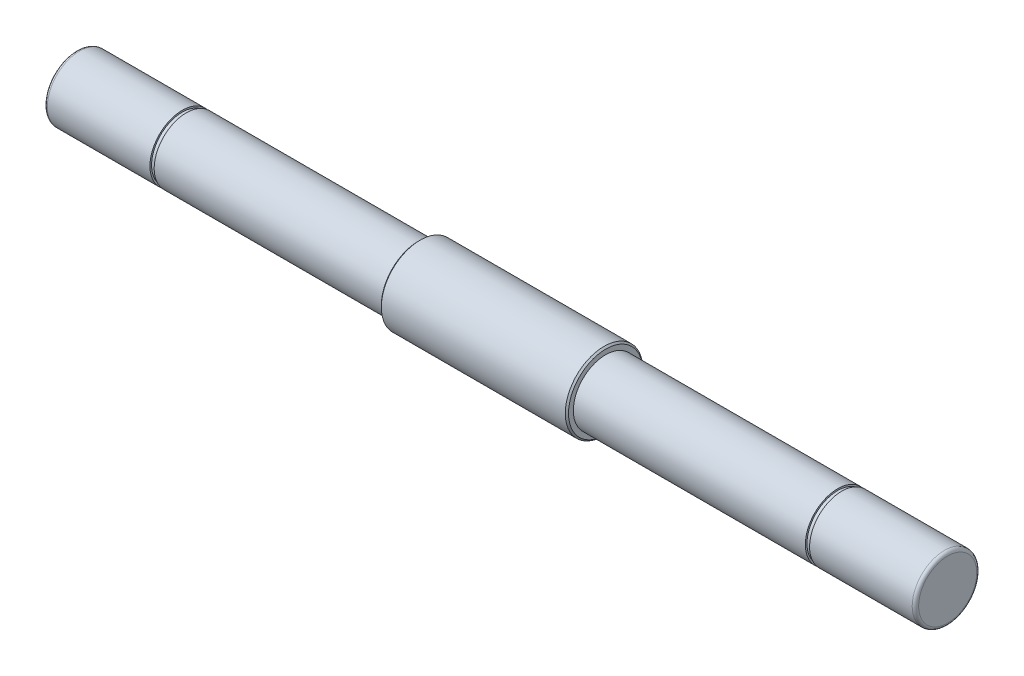
SolidWorks part; units mm, degrees
ref_plane "Front Plane" through (0, 0, 0) normal (0, 0, 1) x (1, 0, 0)
ref_plane "Top Plane" through (0, 0, 0) normal (0, 1, 0) x (1, 0, 0)
ref_plane "Right Plane" through (0, 0, 0) normal (1, 0, 0) x (0, 0, -1)
sketch "Sketch1" plane through (0, 0, 0) normal (0, 1, 0) x (1, 0, 0)
  line L0 (-135, 0) -> (135, 0) construction
  line L1 (-135, 0) -> (-135, 10)
  line L4 (0, 0) -> (0, 68.7304) construction
  line L5 (-135, 10) -> (-102.2, 10)
  line L6 (-29, 10) -> (-29, 12)
  line L7 (-29, 12) -> (29, 12)
  line L9 (-102.2, 10) -> (-102.2, 9.5)
  line L10 (-102.2, 9.5) -> (-100.9, 9.5)
  line L11 (-100.9, 9.5) -> (-100.9, 10)
  line L12 (-100.9, 10) -> (-29, 10)
  line L13 (100.9, 10) -> (29, 10)
  line L14 (100.9, 9.5) -> (100.9, 10)
  line L15 (102.2, 9.5) -> (100.9, 9.5)
  line L16 (102.2, 10) -> (102.2, 9.5)
  line L17 (29, 10) -> (29, 12)
  line L18 (135, 10) -> (102.2, 10)
  line L19 (135, 8) -> (135, 10)
  line L20 (135, 10) -> (135, 8)
  line L21 (135, 0) -> (135, 10)
  line L22 (-135, 0) -> (135, 0)
  point P19 (0, 12)
  point P27 (29, 11)
  dimension "D1" = 270
  dimension "D2" = 24
  dimension "D3" = 20
  dimension "D7" = 19
  dimension "D8" = 1.3
  dimension "D6" = 58
  dimension "D4" = 73.2
revolve "Revolve1" add sketch "Sketch1" angle 360 about L22
chamfer "Chamfer1" distance 0.5 angle 45 2 edges at (29, 0, 12) (-29, 0, 12)
fillet "Fillet1" radius 1 2 edges at (135, 0, 10) (-135, 0, 10)
equation "\"d_ext_rouleau\"= 90"
equation "\"epaisseur_rouleau\"=80"
equation "\"alesage-rouleau\"= 52"
equation "\"jeu_dent_rouleau\"= 2"
equation "\"profondeur_dent_rouleau\"=4"
equation "\"n_dent_roueau\"= 15"
equation "\"B_roulement_rouleau\"= 12"
equation "\"F_anneau_alesage_rouleau\"=1.85"
equation "\"G_anneau_alesage_rouleau\"=47.5"
equation "\"K_anneau_alesage_rouleau\"=3.75"
equation "\"d_vis_flasque_rouleau\"=5"
equation "\"h_matrice\"= 22"
equation "\"d_matrice\"= 220"
equation "\"d_granulat\"= 8"
equation "\"zone_vide_matrice\" = 48"
equation "\"d_alesage_matrice\"=20"
equation "\"a_clavette_alesage_matrice\"=6"
equation "\"D2@Sketch1\"=\"d_int_roulement_rouleau\" + 4"
equation "\"L_arbre_rouleau\" = 270"
equation "\"D1@Sketch1\"=\"L_arbre_rouleau\""
equation "\"g_anneau_arbre_rouleau\"=19"
equation "\"D7@Sketch1\"=\"g_anneau_arbre_rouleau\""
equation "\"f_anneau_arbre_rouleau\"=1.3"
equation "\"D8@Sketch1\"=\"f_anneau_arbre_rouleau\""
equation "\"k_anneau_arbre_rouleau\"=1.5"
equation "\"d_ext_roulement_rouleau\"= 42"
equation "\"d_int_roulement_rouleau\"= 20"
equation "\"D6@Sketch1\"=\"zone_vide_matrice\"+10"
